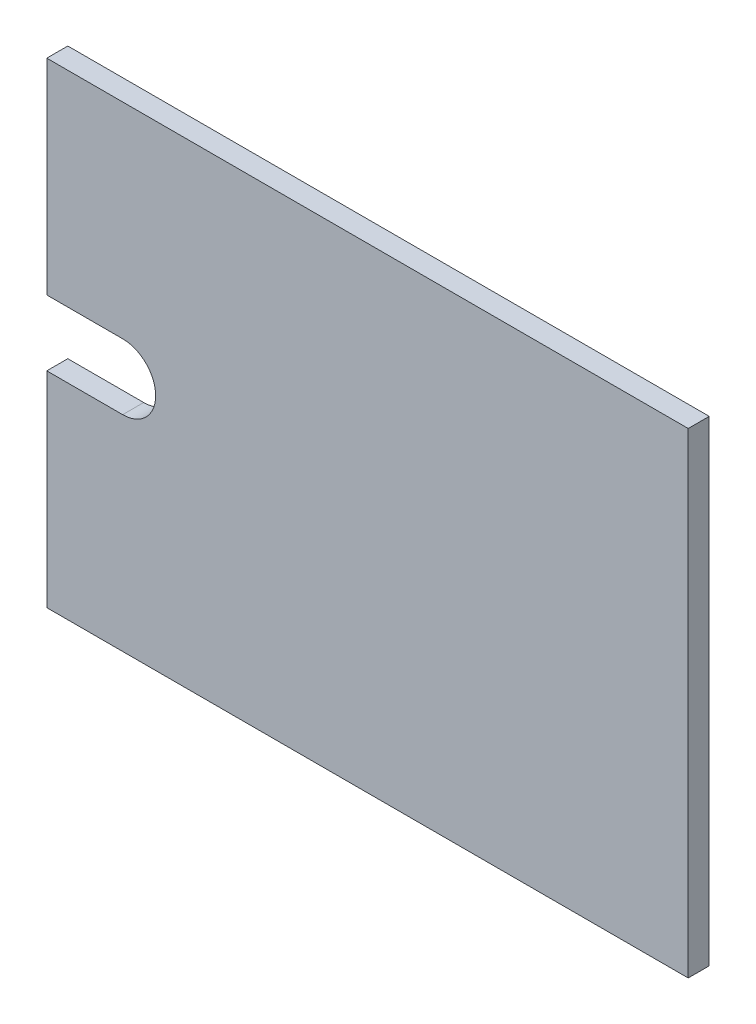
SolidWorks part; units mm, degrees
material "Acrylic (Medium-high impact)"
ref_plane "Front Plane" through (0, 0, 0) normal (0, 0, 1) x (1, 0, 0)
ref_plane "Top Plane" through (0, 0, 0) normal (0, 1, 0) x (1, 0, 0)
ref_plane "Right Plane" through (0, 0, 0) normal (1, 0, 0) x (0, 0, -1)
sketch "Sketch1" plane through (0, 0, 0) normal (0, 0, 1) x (1, 0, 0)
  line L1 (-15.5, 11.5) -> (15.5, 11.5)
  line L2 (-15.5, 11.5) -> (-15.5, -11.5)
  line L3 (-15.5, -11.5) -> (15.5, -11.5)
  line L4 (15.5, 11.5) -> (15.5, -11.5)
  line L5 (-15.5, 11.5) -> (15.5, -11.5) construction
  line L6 (-15.5, -11.5) -> (15.5, 11.5) construction
  point P0 (0, 0)
  dimension "D1" = 23
  dimension "D2" = 31
extrude "Boss-Extrude1" add sketch "Sketch1" along normal blind 1.016
sketch "Sketch2" plane through (0, 0, 0) normal (0, 0, -1) x (-1, 0, 0)
  line L1 (15, 15.004) -> (15, 1.5915) construction
  line L2 (11.825, 1.5875) -> (15.5, 1.5875)
  line L3 (15.5, 11.5) -> (15.5, -11.5) construction
  line L4 (15.5, 1.5875) -> (15.5, -1.5875)
  line L5 (11.8313, -1.5875) -> (15.5, -1.5875)
  arc A0 (11.825, 1.5875) -> (11.8313, -1.5875) centre (11.825, 0) ccw
  dimension "D2" = 3.175
  dimension "D1" = 3.175
extrude "Cut-Extrude1" cut sketch "Sketch2" against normal through all
